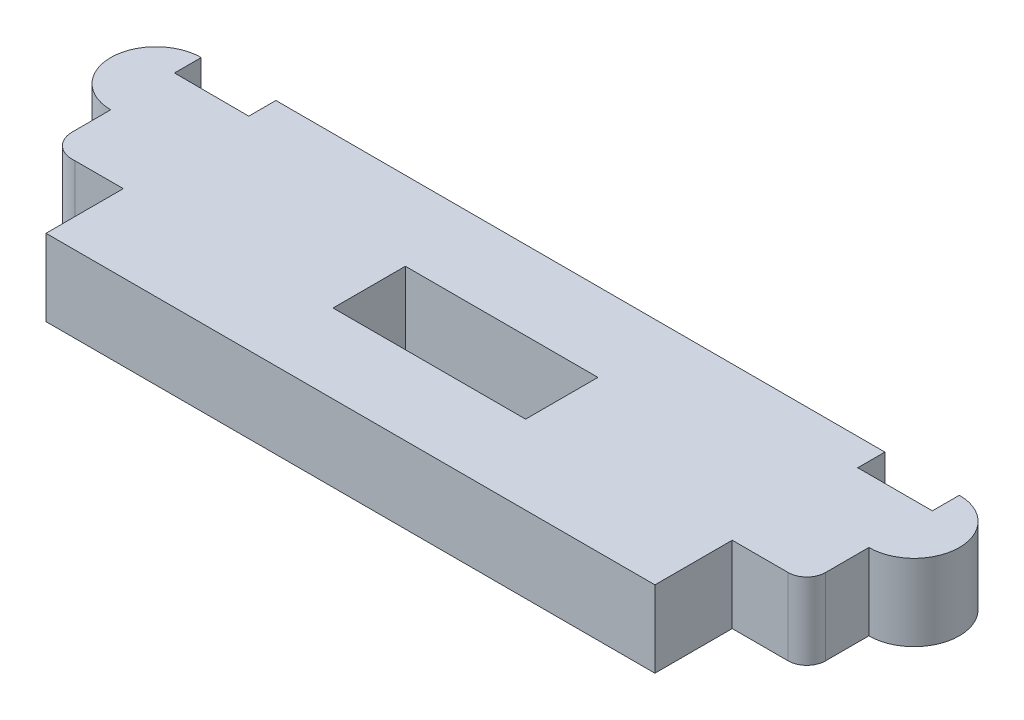
SolidWorks part; units mm, degrees
ref_plane "Front Plane" through (0, 0, 0) normal (0, 0, 1) x (1, 0, 0)
ref_plane "Top Plane" through (0, 0, 0) normal (0, 1, 0) x (1, 0, 0)
ref_plane "Right Plane" through (0, 0, 0) normal (1, 0, 0) x (0, 0, -1)
sketch "Sketch2" plane through (0, 0, 0) normal (0, 1, 0) x (1, 0, 0)
  line L17 (12.626, -1.7445) -> (12.626, -4.9504)
  line L18 (12.626, -4.9504) -> (-12.6291, -4.9504)
  line L19 (-12.6291, -4.9504) -> (-12.6291, -1.7445)
  line L20 (-12.6291, -1.7445) -> (-14.6231, -1.7445)
  line L21 (-15.7222, -0.7699) -> (-15.7222, 0.8268)
  line L22 (-15.7222, 4.5812) -> (-15.7222, 3.4718)
  line L23 (-15.7222, 3.4718) -> (-12.6313, 3.4609)
  line L24 (-12.6313, 3.4609) -> (-12.6313, 4.587)
  line L25 (-12.6313, 4.587) -> (12.626, 4.587)
  line L26 (12.626, 4.587) -> (12.626, 3.4609)
  line L27 (12.626, 3.4609) -> (15.7205, 3.4609)
  line L28 (15.7205, 3.4609) -> (15.7205, 4.5812)
  line L29 (15.7205, 0.8265) -> (15.7205, -0.9727)
  line L30 (14.9316, -1.7445) -> (12.626, -1.7445)
  line L31 (3.9929, 1.3183) -> (3.9929, -1.6817)
  line L32 (3.9929, -1.6817) -> (-3.9929, -1.6817)
  line L33 (-3.9929, -1.6817) -> (-3.9929, 1.3183)
  line L34 (-3.9929, 1.3183) -> (3.9929, 1.3183)
  arc A0 (-15.7222, -0.7699) -> (-14.6231, -1.7445) centre (-14.7405, -0.7699) ccw
  arc A1 (-15.7222, 4.5812) -> (-15.7222, 0.8268) centre (-15.7222, 2.704) ccw
  arc A2 (15.7205, -0.9727) -> (14.9316, -1.7445) centre (14.9485, -0.9727) cw
  arc A3 (15.7205, 0.8265) -> (15.7205, 4.5812) centre (15.7205, 2.7039) ccw
extrude "Boss-Extrude1" add sketch "Sketch2" along normal blind 3.175
